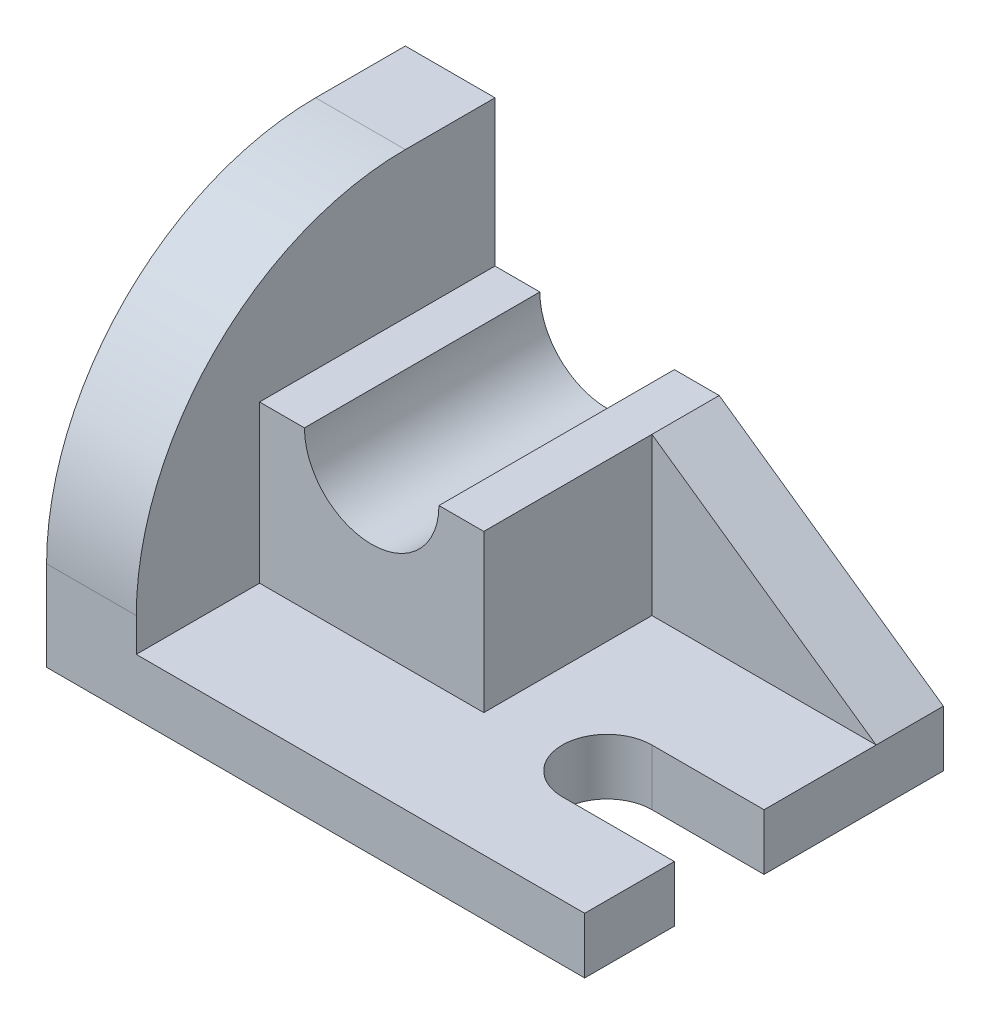
SolidWorks part; units mm, degrees
ref_plane "Front Plane" through (0, 0, 0) normal (0, 0, 1) x (1, 0, 0)
ref_plane "Top Plane" through (0, 0, 0) normal (0, 1, 0) x (1, 0, 0)
ref_plane "Right Plane" through (0, 0, 0) normal (1, 0, 0) x (0, 0, -1)
sketch "Sketch2" plane through (0, 0, 0) normal (0, 1, 0) x (1, 0, 0)
  line L1 (0, 0) -> (96, 0)
  line L2 (0, 0) -> (0, 64)
  line L3 (0, 64) -> (96, 64)
  line L4 (96, 0) -> (96, 64)
  dimension "D1" = 96
  dimension "D2" = 96
  dimension "D3" = 64
extrude "Boss-Extrude1" add sketch "Sketch2" along normal blind 10
sketch "Sketch3" plane through (0, 10, 0) normal (0, 1, 0) x (1, 0, 0)
  line L0 (96, 24) -> (76, 24) construction
  line L1 (96, 0) -> (96, 64) construction
  line L2 (96, 16) -> (76, 16)
  line L3 (96, 32) -> (76, 32)
  line L4 (0, 0) -> (96, 0) construction
  arc A0 (96, 16) -> (96, 32) centre (96, 24) ccw
  arc A1 (76, 32) -> (76, 16) centre (76, 24) ccw
  point P4 (86, 24)
  dimension "D2" = 8
  dimension "D1" = 20
  dimension "D3" = 16
extrude "Cut-Extrude3" cut sketch "Sketch3" against normal blind 13
ref_plane "Plane1" through (0, 0, 0) normal (0, 0, 1) x (1, 0, 0)
sketch "Sketch7" plane through (0, 0, 0) normal (-1, 0, 0) x (0, 0, 1)
  line L1 (-64, 0) -> (0, 0)
  line L2 (-64, 0) -> (-64, 64)
  line L3 (-64, 64) -> (-48, 64)
  line L4 (0, 0) -> (0, 16)
  arc A0 (-48, 64) -> (0, 16) centre (-48, 16) cw
  dimension "D2" = 48
  dimension "D1" = 64
extrude "Boss-Extrude4" add sketch "Sketch7" against normal blind 16 contours L2 L1 L4 A0 L3
sketch "Sketch8" plane through (0, 10, 0) normal (0, 1, 0) x (1, 0, 0)
  line L0 (16, 0) -> (96, 0) construction
  line L1 (16, 64) -> (56, 64)
  line L2 (16, 64) -> (16, 22)
  line L3 (16, 22) -> (56, 22)
  line L4 (56, 64) -> (56, 22)
  dimension "D1" = 40
  dimension "D2" = 22
extrude "Boss-Extrude6" add sketch "Sketch8" along normal blind 28 contours L2 L1 L4 L3
sketch "Sketch9" plane through (0, 0, -22) normal (0, 0, 1) x (1, 0, 0)
  line L0 (16, 38) -> (56, 38) construction
  circle A0 centre (36, 38) radius 12
  dimension "D1" = 24
extrude "Cut-Extrude4" cut sketch "Sketch9" against normal up to next
ref_plane "Plane2" through (56, 10, -64) normal (0, -1, 0) x (-1, 0, 0)
ref_plane "Plane3" through (56, 10, -64) normal (0, -1, 0) x (-1, 0, 0)
ref_plane "Plane4" through (56, 38, -64) normal (0, -1, 0) x (-1, 0, 0)
ref_plane "Plane5" through (56, 10, -64) normal (0, -1, 0) x (-1, 0, 0)
sketch "Sketch15" plane through (0, 0, -64) normal (0, 0, -1) x (-1, 0, 0)
  line L0 (-96, 10) -> (-56, 38)
  line L1 (-56, 38) -> (-56, 10)
  line L2 (-56, 10) -> (-96, 10)
extrude "Boss-Extrude7" add sketch "Sketch15" against normal blind 12
